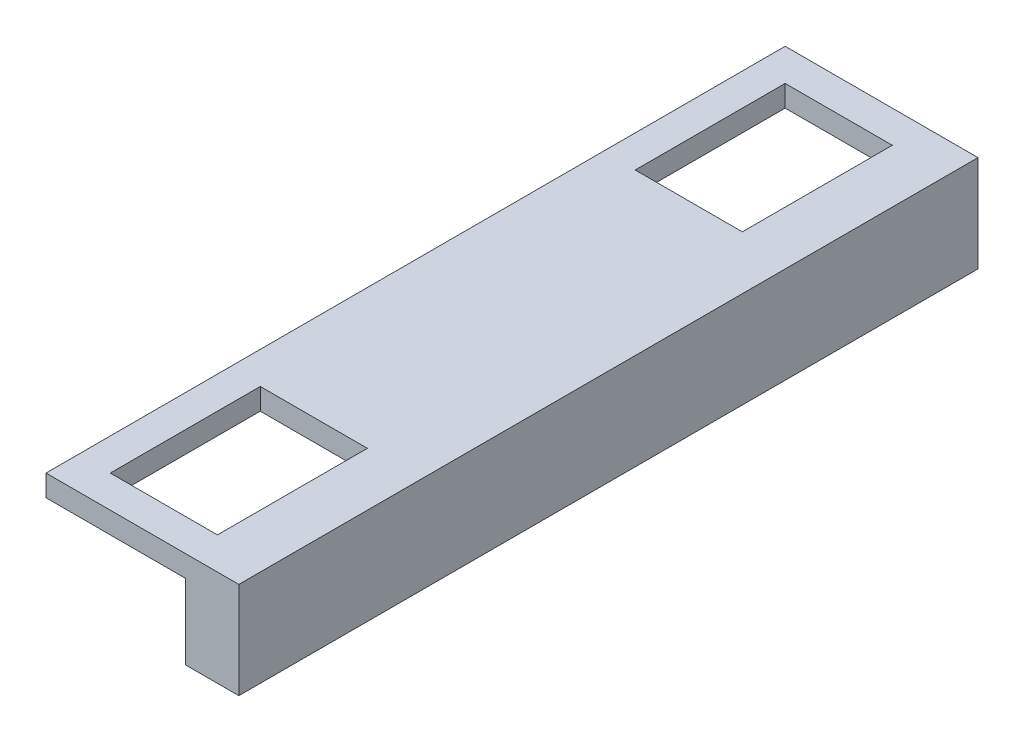
SolidWorks part; units mm, degrees
material "ABS"
ref_plane "Front Plane" through (0, 0, 0) normal (0, 0, 1) x (1, 0, 0)
ref_plane "Top Plane" through (0, 0, 0) normal (0, 1, 0) x (1, 0, 0)
ref_plane "Right Plane" through (0, 0, 0) normal (1, 0, 0) x (0, 0, -1)
sketch "Sketch1" plane through (0, 0, 0) normal (0, 0, 1) x (1, 0, 0)
  line L3 (2.5, 1) -> (2.5, 8)
  line L4 (2.5, 8) -> (-7.5, 8)
  line L5 (-7.5, 8) -> (-7.5, 10)
  line L6 (-7.5, 10) -> (7.5, 10)
  line L8 (7.5, 10) -> (7.5, 1)
  line L9 (7.5, 1) -> (2.5, 1)
  point P4 (0, 0)
  dimension "D4" = 7
  dimension "D5" = 2
extrude "Boss-Extrude1" add sketch "Sketch1" against normal blind 69
sketch "Sketch2" plane through (-7.5, 0, 0) normal (-1, 0, 0) x (0, 0, 1)
  line L4 (0, 8) -> (0, 10)
  line L5 (0, 10) -> (-69, 10)
  line L6 (-69, 10) -> (-69, 8)
  line L7 (-69, 8) -> (0, 8)
  line L8 (0, 8) -> (0, 10)
  line L9 (0, 10) -> (-69, 10)
  line L10 (-69, 10) -> (-69, 8)
  line L11 (-69, 8) -> (0, 8)
  dimension "D1" = 0
extrude "Boss-Extrude2" add sketch "Sketch2" along normal blind 3
sketch "Sketch3" plane through (2.5, 0, 0) normal (-1, 0, 0) x (0, 0, 1)
  line L0 (-69, 1) -> (0, 1) construction
  line L9 (-34.5, 1) -> (-34.5, 8) construction
  line L10 (-69, 8) -> (0, 8) construction
  line L11 (-37, 1) -> (-32, 1)
  line L12 (-37, 1) -> (-37, 8)
  line L13 (-37, 8) -> (-32, 8)
  line L14 (-32, 8) -> (-32, 1)
  point P0 (0, 0)
  point P10 (-34.5, 1)
  dimension "D2" = 5
extrude "Boss-Extrude4" add sketch "Sketch3" along normal blind 13
sketch "Sketch5" plane through (0, 0, -32) normal (0, 0, 1) x (1, 0, 0)
  line L0 (-2.5, 4.5) -> (2.5, 4.5) construction
  line L3 (2.5, 1) -> (2.5, 8) construction
  circle A0 centre (-2.5, 4.5) radius 1.5
  dimension "D1" = 3
  dimension "D2" = 5
extrude "Boss-Extrude5" add sketch "Sketch5" along normal blind 3
sketch "Sketch8" plane through (0, 10, 0) normal (0, 1, 0) x (1, 0, 0)
  line L0 (7.5, 0) -> (-2.5, 0) construction
  line L1 (7.5, 0) -> (-10.5, 0) construction
  line L2 (-2.5, 0) -> (-2.5, 3) construction
  line L3 (-7.5, 3) -> (2.5, 3)
  line L5 (-7.5, 3) -> (-7.5, 17)
  line L6 (-7.5, 17) -> (2.5, 17)
  line L7 (2.5, 17) -> (2.5, 3)
  point P9 (-2.5, 3)
  dimension "D1" = 10
  dimension "D2" = 3
  dimension "D3" = 10
  dimension "D4" = 14
extrude "Cut-Extrude1" cut sketch "Sketch8" against normal through all
ref_plane "Plane2" through (0, 0, -34.5) normal (0, 0, 1) x (1, 0, 0)
mirror "Mirror1" about plane through (0, 0, -34.5) normal (0, 0, 1) of "Cut-Extrude1", "Boss-Extrude5"
sketch "Sketch9" plane through (0, 1, 0) normal (0, -1, 0) x (1, 0, 0)
  line L0 (7.5, -34.5) -> (5, -34.5) construction
  line L1 (7.5, -69) -> (7.5, 0) construction
  line L2 (5, -44.5) -> (5, -24.5) construction
  line L3 (5, -24.5) -> (5, -44.5) construction
  line L4 (6.6, -24.5) -> (6.6, -44.5)
  line L5 (3.4, -24.5) -> (3.4, -44.5)
  arc A0 (6.6, -24.5) -> (3.4, -24.5) centre (5, -24.5) ccw
  arc A1 (3.4, -44.5) -> (6.6, -44.5) centre (5, -44.5) ccw
  point P4 (5, -34.5)
  point P7 (5, -34.5)
  dimension "D1" = 2.5
  dimension "D2" = 20
  dimension "D3" = 3.2
extrude "Cut-Extrude2" cut sketch "Sketch9" against normal blind 3
